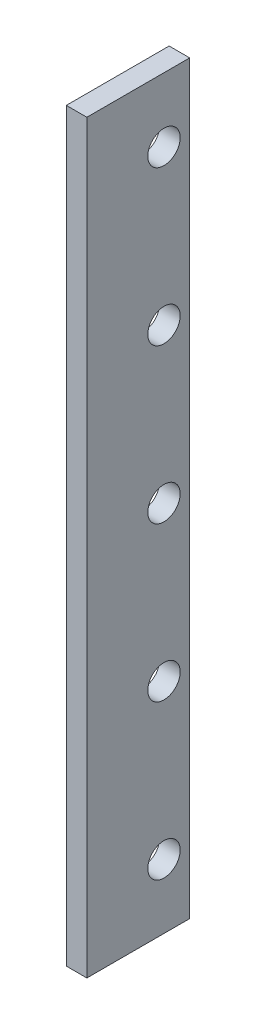
SolidWorks part; units mm, degrees
ref_plane "Front Plane" through (0, 0, 0) normal (1, 0, 0) x (0, 1, 0)
ref_plane "Top Plane" through (0, 0, 0) normal (0, 0, 1) x (0, 1, 0)
ref_plane "Right Plane" through (0, 0, 0) normal (0, 1, 0) x (-1, 0, 0)
sketch "Sketch2" plane through (0, 0, 0) normal (0, 1, 0) x (-1, 0, 0)
  line L1 (-8, -40) -> (8, -40)
  line L2 (-8, -40) -> (-8, 40)
  line L3 (-8, 40) -> (8, 40)
  line L4 (8, -40) -> (8, 40)
  line L5 (-8, -40) -> (8, 40) construction
  line L6 (-8, 40) -> (8, -40) construction
  point P0 (0, 0)
  dimension "D1" = 80
  dimension "D2" = 16
extrude "Boss-Extrude1" add sketch "Sketch2" along normal mid plane 580
sketch "Sketch3" plane through (8, 0, 0) normal (1, 0, 0) x (0, 1, 0)
  line L0 (-290, 40) -> (-290, -40) construction
  line L1 (290, -40) -> (-290, -40) construction
  circle A0 centre (-240, -20) radius 12.6
  point P4 (0, 0)
  point P6 (-227.9449, -40)
  dimension "D3" = 25.2
  dimension "D1" = 50
  dimension "D2" = 20
extrude "Cut-Extrude1" cut sketch "Sketch3" against normal through all
pattern_linear "LPattern1" count 5 spacing 120 along (0, 1, 0) of "Cut-Extrude1"
